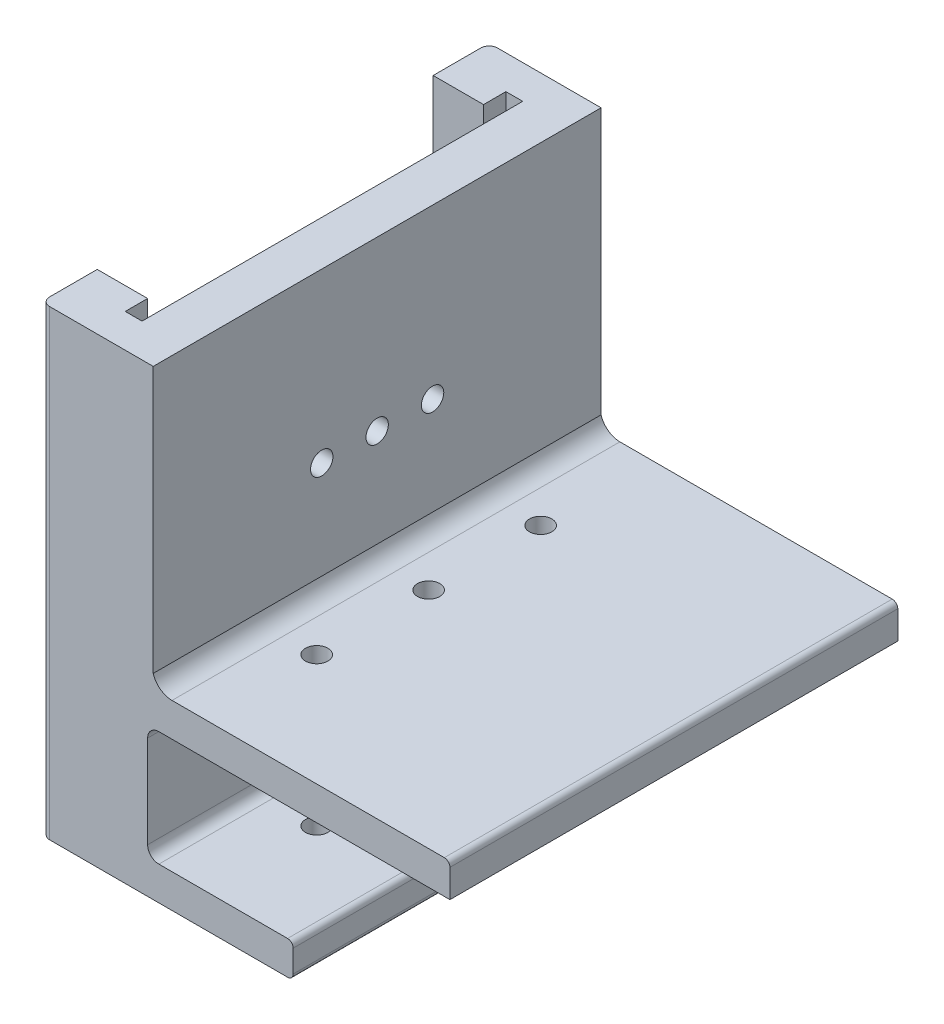
SolidWorks part; units mm, degrees
ref_plane "Front Plane" through (0, 0, 0) normal (0, 0, 1) x (1, 0, 0)
ref_plane "Top Plane" through (0, 0, 0) normal (0, 1, 0) x (1, 0, 0)
ref_plane "Right Plane" through (0, 0, 0) normal (1, 0, 0) x (0, 0, -1)
sketch "Sketch1" plane through (0, 0, 0) normal (0, 0, 1) x (1, 0, 0)
  line L0 (0, -8.25) -> (0, 8.25)
  line L1 (2, 10.25) -> (54, 10.25)
  line L2 (2, -10.25) -> (25, -10.25)
  line L3 (54, 10.25) -> (54, 15.25)
  line L4 (53, 16.25) -> (4, 16.25)
  line L5 (26, -11.25) -> (26, -15.25)
  line L6 (25, -16.25) -> (-19, -16.25)
  line L7 (14.4252, -25.8312) -> (14.9286, -25.3278)
  line L8 (-19, -16.25) -> (-19, 16.25)
  line L9 (-19, 16.25) -> (4, 16.25)
  arc A0 (0, 8.25) -> (2, 10.25) centre (2, 8.25) cw
  arc A1 (0, -8.25) -> (2, -10.25) centre (2, -8.25) ccw
  arc A2 (54, 15.25) -> (53, 16.25) centre (53, 15.25) ccw
  arc A3 (25, -10.25) -> (26, -11.25) centre (25, -11.25) cw
  arc A4 (26, -15.25) -> (25, -16.25) centre (25, -15.25) cw
  point P4 (0, 0)
  point P8 (0, 10.25)
  point P12 (0, -10.25)
  point P18 (54, 16.25)
  point P21 (26, -10.25)
  point P24 (26, -16.25)
  dimension "D3" = 2
  dimension "D5" = 2
  dimension "D10" = 1
  dimension "D1" = 20.5
  dimension "D2" = 54
  dimension "D4" = 26
  dimension "D6" = 6
  dimension "D7" = 50
  dimension "D8" = 6
  dimension "D9" = 45
extrude "Boss-Extrude2" add sketch "Sketch1" along normal blind 80 contours A4 L5 A3 L2 A1 L0 A0 L1 L3 A2 L4 L9 L8 L6
sketch "Sketch3" plane through (0, 16.25, 0) normal (0, 1, 0) x (1, 0, 0)
  line L0 (53, 0) -> (-19, 0) construction
  line L1 (0, -80) -> (0, 0) construction
  circle A0 centre (10.2, -20) radius 2
  circle A1 centre (10.2, -40) radius 2
  circle A2 centre (10.2, -60) radius 2
  dimension "D1" = 20
  dimension "D3" = 3
  dimension "D2" = 10.2
extrude "Cut-Extrude2" cut sketch "Sketch3" against normal blind 80 contours A1 | A2 | A0
sketch "Sketch4" plane through (0, 16.25, 0) normal (0, 1, 0) x (1, 0, 0)
  line L0 (53, -80) -> (-19, -80) construction
  line L1 (-19, 0) -> (1, 0)
  line L2 (-19, 0) -> (-19, -80)
  line L3 (-19, -80) -> (1, -80)
  line L4 (1, 0) -> (1, -80)
  dimension "D1" = 20
extrude "Boss-Extrude3" add sketch "Sketch4" along normal blind 50
sketch "Sketch5" plane through (0, 0, 80) normal (0, 0, 1) x (1, 0, 0)
  line L4 (1, 20.75) -> (1, 16.25)
  line L5 (1, 16.25) -> (4.3541, 16.25)
  line L6 (1, 20.75) -> (1, 16.25)
  arc A0 (1, 20.75) -> (4.3541, 16.25) centre (4.3541, 19.75) ccw
  point P10 (1, 16.25)
  line M11 (53, 16.25) -> (1, 16.25)
  line M12 (1, 16.25) -> (1, 66.25)
  dimension "D1" = 3.5
extrude "Boss-Extrude4" add sketch "Sketch5" against normal blind 80 contours A0 M12 M11
sketch "Sketch6" plane through (0, 66.25, 0) normal (0, 1, 0) x (1, 0, 0)
  line L1 (-7, -70) -> (-19, -70)
  line L2 (-7, -70) -> (-7, -10)
  line L3 (-7, -10) -> (-19, -10)
  line L4 (-19, -70) -> (-19, -10)
  line L5 (-19, -80) -> (1, -80) construction
  line L6 (-19, -70) -> (-19, -80)
  line L7 (-17.5, -80) -> (1, -80)
  line L8 (1, -80) -> (1, 0)
  line L9 (1, 0) -> (-17.5, 0)
  line L10 (-19, -1.5) -> (-19, -78.5)
  line L11 (-19, 0) -> (-19, -80) construction
  line L12 (-19, -80) -> (1, -80)
  line L13 (-19, -80) -> (-19, 0)
  line L14 (-19, 0) -> (1, 0)
  line L15 (1, -80) -> (1, 0)
  arc A0 (-17.5, 0) -> (-19, -1.5) centre (-17.5, -1.5) ccw
  arc A1 (-17.5, -80) -> (-19, -78.5) centre (-17.5, -78.5) cw
  point P18 (-19, 0)
  line M5 (-19, 0) -> (-19, -80)
  line M6 (-19, -80) -> (1, -80)
  line M8 (1, 0) -> (-19, 0)
  dimension "D3" = 1.5
  dimension "D1" = 60
  dimension "D2" = 10
  dimension "D4" = 12
  dimension "D5" = 0
extrude "Cut-Extrude4" cut sketch "Sketch6" against normal blind 90 contours L2 L3 L1 M5 | A1 L6 M6 | A0 M8 M5
sketch "Sketch7" plane through (0, 66.25, 0) normal (0, 1, 0) x (1, 0, 0)
  line L0 (-17.5, -80) -> (1, -80) construction
  line L1 (-10, -74) -> (-7, -74)
  line L2 (-10, -74) -> (-10, -6)
  line L3 (-10, -6) -> (-7, -6)
  line L4 (-7, -74) -> (-7, -6)
  line L5 (-7, -70) -> (-7, -10) construction
  dimension "D1" = 68
  dimension "D2" = 6
  dimension "D3" = 0
  dimension "D4" = 3
extrude "Cut-Extrude5" cut sketch "Sketch7" against normal blind 90
sketch "Sketch9" plane through (1, 0, 0) normal (1, 0, 0) x (0, 0, -1)
  line L0 (-80, 66.25) -> (0, 66.25) construction
  line L2 (-40, 66.25) -> (-40, 18.75) construction
  line L3 (0, 18.75) -> (-80, 18.75) construction
  line L4 (0, 66.25) -> (0, 18.75) construction
  circle A0 centre (-49.9, 36.25) radius 2
  circle A1 centre (-30.1, 36.25) radius 2
  dimension "D1" = 30
  dimension "D2" = 40
  dimension "D4" = 9.9
  dimension "D3" = 2
extrude "Cut-Extrude6" cut sketch "Sketch9" against normal blind 90
sketch "Sketch11" plane through (1, 0, 0) normal (1, 0, 0) x (0, 0, -1)
  line L0 (-80, 66.25) -> (0, 66.25) construction
  circle A0 centre (-40, 36.25) radius 2
  circle A1 centre (-30.1, 36.25) radius 2 construction
  dimension "D1" = 9.9
  dimension "D2" = 30
extrude "Cut-Extrude7" cut sketch "Sketch11" against normal blind 90
